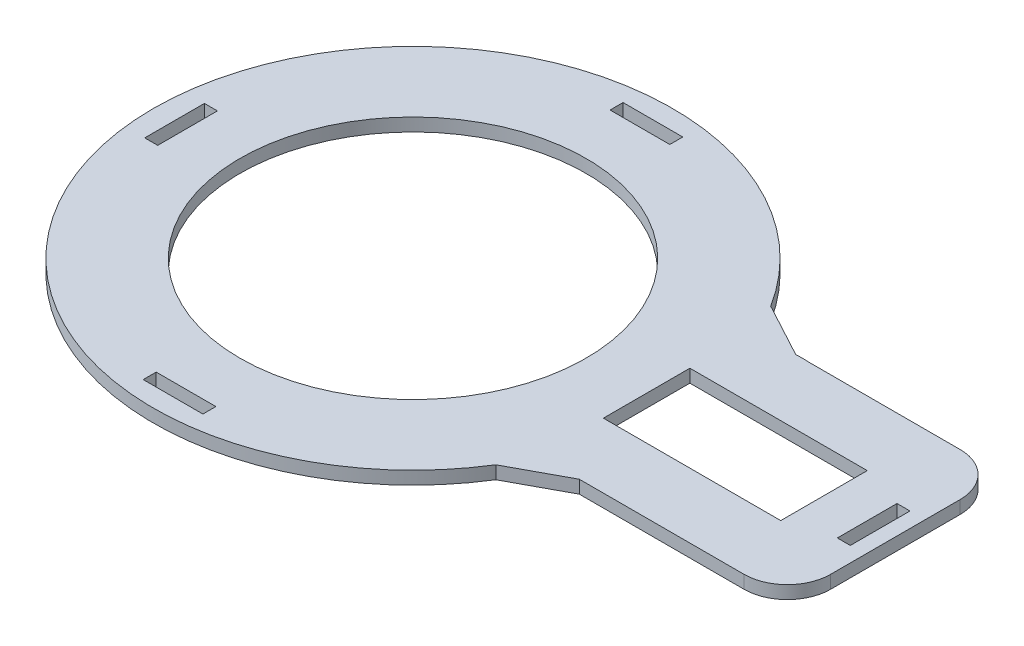
SolidWorks part; units mm, degrees
ref_plane "Спереди" through (0, 0, 0) normal (0, 0, 1) x (1, 0, 0)
ref_plane "Сверху" through (0, 0, 0) normal (0, 1, 0) x (1, 0, 0)
ref_plane "Справа" through (0, 0, 0) normal (1, 0, 0) x (0, 0, -1)
other "Configuration Table"
sketch "Эскиз2" plane through (0, 0, 0) normal (0, 1, 0) x (1, 0, 0)
  line L0 (50.9013, -31.7657) -> (63.5214, -24.9562)
  line L1 (0, 0) -> (65, 0) construction
  line L2 (50.9013, 31.7657) -> (63.5214, 24.9562)
  arc A0 (50.9013, 31.7657) -> (50.9013, -31.7657) centre (0, 0) ccw
  arc A1 (63.5214, -24.9562) -> (63.5214, 24.9562) centre (65, 0) ccw
  dimension "D1" = 120
  dimension "D2" = 50
  dimension "D3" = 65
extrude "Бобышка-Вытянуть1" add sketch "Эскиз2" along normal blind 3
sketch "Эскиз3" plane through (0, 3, 0) normal (0, 1, 0) x (1, 0, 0)
  line L0 (0, -64.6867) -> (0, 64.6867) construction
  line L1 (-104.0068, 0) -> (104.0068, 0) construction
  line L2 (-6.9, 52.4569) -> (6.9, 52.4569)
  line L3 (-6.9, -55.4569) -> (6.9, -55.4569)
  line L4 (-6.9, -55.4569) -> (-6.9, -52.4569)
  line L5 (-6.9, -52.4569) -> (6.9, -52.4569)
  line L6 (6.9, -55.4569) -> (6.9, -52.4569)
  line L7 (-6.9, -55.4569) -> (6.9, -52.4569) construction
  line L8 (-6.9, -52.4569) -> (6.9, -55.4569) construction
  line L9 (6.9, 55.4569) -> (6.9, 52.4569)
  line L10 (-6.9, 55.4569) -> (6.9, 55.4569)
  line L11 (-6.9, 55.4569) -> (-6.9, 52.4569)
  line L13 (-55.1052, -6.9) -> (-52.1052, -6.9)
  line L14 (-55.1052, -6.9) -> (-55.1052, 6.9)
  line L15 (-55.1052, 6.9) -> (-52.1052, 6.9)
  line L16 (-52.1052, -6.9) -> (-52.1052, 6.9)
  line L17 (-55.1052, -6.9) -> (-52.1052, 6.9) construction
  line L18 (-55.1052, 6.9) -> (-52.1052, -6.9) construction
  line L19 (85.5598, -6.9) -> (82.5598, -6.9)
  line L20 (85.5598, -6.9) -> (85.5598, 6.9)
  line L21 (85.5598, 6.9) -> (82.5598, 6.9)
  line L22 (82.5598, -6.9) -> (82.5598, 6.9)
  line L23 (85.5598, -6.9) -> (82.5598, 6.9) construction
  line L24 (85.5598, 6.9) -> (82.5598, -6.9) construction
  point P0 (0, -53.9569)
  point P3 (84.0598, 0)
  point P5 (0, 0)
  point P10 (0, 0)
  point P15 (-53.6052, 0)
  point P25 (-59.6735, 0)
  point P27 (90.0559, 0)
  dimension "D1" = 3
  dimension "D2" = 13.8
  dimension "D3" = 13.8
  dimension "D4" = 3
  dimension "D5" = 13.8
  dimension "D6" = 3
extrude "Вырез-Вытянуть1" cut sketch "Эскиз3" against normal blind 10
sketch "Эскиз4" plane through (0, 3, 0) normal (0, 1, 0) x (1, 0, 0)
  line L1 (63.5214, 24.9562) -> (101.5214, 24.9562)
  line L2 (63.5214, 24.9562) -> (63.5214, -25)
  line L3 (63.5214, -25) -> (101.5214, -25)
  line L4 (111.5214, 14.9562) -> (111.5214, -15)
  arc A0 (63.5214, -24.9562) -> (63.5214, 24.9562) centre (65, 0) ccw construction
  arc A1 (63.5214, -24.9562) -> (63.5214, 24.9562) centre (65, 0) ccw
  arc A2 (101.5214, -25) -> (111.5214, -15) centre (101.5214, -15) ccw
  arc A3 (111.5214, 14.9562) -> (101.5214, 24.9562) centre (101.5214, 14.9562) ccw
  point P10 (111.5214, 24.9562)
  dimension "D2" = 10
  dimension "D1" = 48
extrude "Бобышка-Вытянуть2" add sketch "Эскиз4" against normal up to surface (3 mm away) contours L1 A3 L4 A2 L3 L2 up to face at (84.0598, 0, 0)
sketch "Эскиз5" plane through (0, 3, 0) normal (0, 1, 0) x (1, 0, 0)
  line L1 (108.0214, -6.9438) -> (105.0214, -6.9438)
  line L2 (108.0214, -6.9438) -> (108.0214, 6.8562)
  line L3 (108.0214, 6.8562) -> (105.0214, 6.8562)
  line L4 (105.0214, -6.9438) -> (105.0214, 6.8562)
  line L5 (108.0214, -6.9438) -> (105.0214, 6.8562) construction
  line L6 (108.0214, 6.8562) -> (105.0214, -6.9438) construction
  line L9 (111.5214, 14.9562) -> (111.5214, -15) construction
  line L11 (66.4786, 24.9562) -> (101.5214, 24.9562) construction
  point P0 (106.5214, -0.0438)
  point P5 (106.1323, 1.5873)
  dimension "D1" = 3
  dimension "D2" = 13.8
  dimension "D3" = 5
  dimension "D4" = 25
extrude "Вырез-Вытянуть2" cut sketch "Эскиз5" against normal blind 20 contours L2 L3 L4 L1
sketch "Эскиз6" plane through (0, 3, 0) normal (0, 1, 0) x (1, 0, 0)
  line L0 (111.5214, 14.9562) -> (111.5214, -15) construction
  line L2 (54.0014, -10) -> (95.0014, -10)
  line L3 (54.0014, -10) -> (54.0014, 10)
  line L4 (54.0014, 10) -> (95.0014, 10)
  line L5 (95.0014, -10) -> (95.0014, 10)
  line L6 (54.0014, -10) -> (95.0014, 10) construction
  line L7 (54.0014, 10) -> (95.0014, -10) construction
  point P0 (74.5014, 0)
  point P3 (74.5014, 0)
  dimension "D1" = 37.02
  dimension "D2" = 41
  dimension "D3" = 20
extrude "Вырез-Вытянуть3" cut sketch "Эскиз6" against normal blind 10
sketch "Эскиз7" plane through (0, 3, 0) normal (0, 1, 0) x (1, 0, 0)
  circle A0 centre (0, 0) radius 40
  dimension "D1" = 80
extrude "Вырез-Вытянуть4" cut sketch "Эскиз7" against normal blind 3 contours A0
